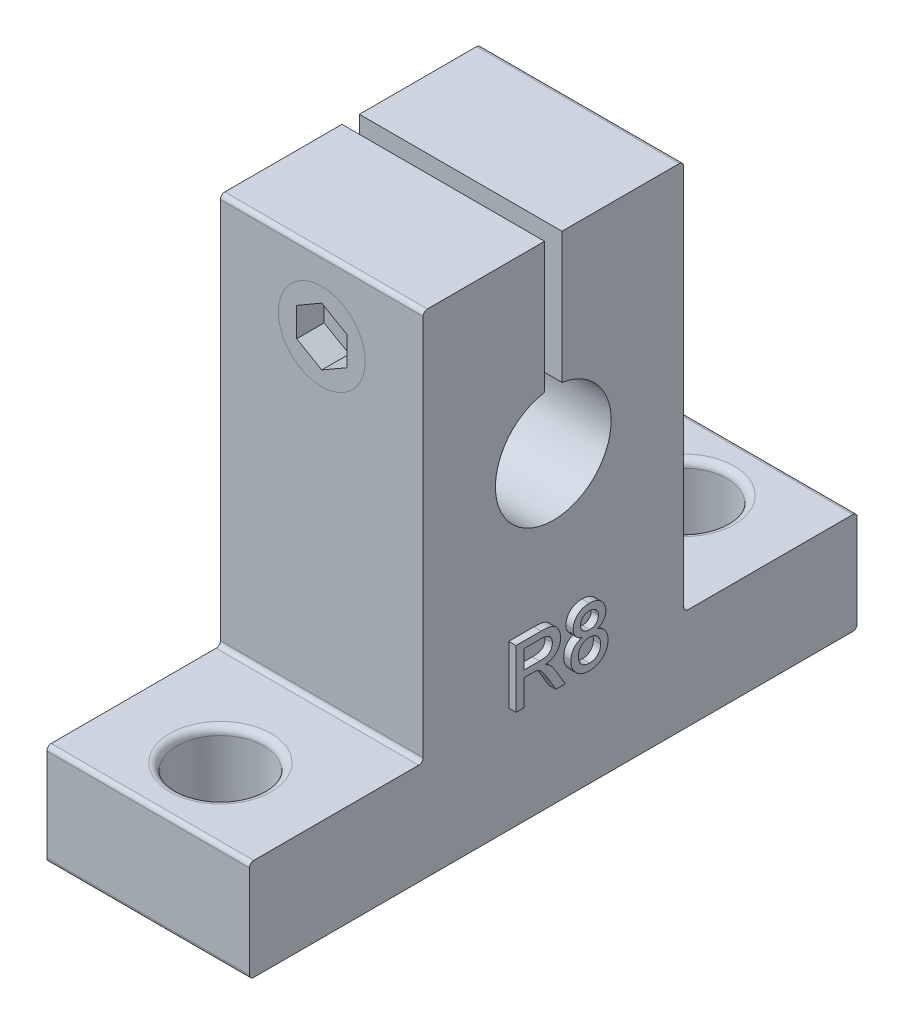
SolidWorks part; units mm, degrees
ref_plane "Спереди" through (0, 0, 0) normal (0, 0, 1) x (1, 0, 0)
ref_plane "Сверху" through (0, 0, 0) normal (0, 1, 0) x (1, 0, 0)
ref_plane "Справа" through (0, 0, 0) normal (1, 0, 0) x (0, 0, -1)
ref_plane "Плоскость1" through (0, 0, 0) normal (1, 0, 0) x (0, 0, -1)
sketch "Эскиз1" plane through (0, 0, 0) normal (1, 0, 0) x (0, 0, -1)
  line L0 (0.3, 7) -> (11.7, 7)
  line L1 (0.3, 0) -> (41.7, 0)
  line L2 (0, 0.3) -> (0, 6.7)
  line L4 (42, 0.3) -> (42, 6.7)
  line L5 (21, 0) -> (21, 7) construction
  line L6 (41.7, 7) -> (30.3, 7)
  line L7 (12, 7.3) -> (12, 33.7)
  line L8 (12.3, 34) -> (29.7, 34)
  line L9 (30, 33.7) -> (30, 7.3)
  line L10 (21, 34) -> (21, 21) construction
  circle A0 centre (21, 21) radius 4
  arc A1 (30.3, 7) -> (30, 7.3) centre (30.3, 7.3) cw
  arc A2 (11.7, 7) -> (12, 7.3) centre (11.7, 7.3) ccw
  arc A3 (41.7, 0) -> (42, 0.3) centre (41.7, 0.3) ccw
  arc A4 (42, 6.7) -> (41.7, 7) centre (41.7, 6.7) ccw
  arc A5 (30, 33.7) -> (29.7, 34) centre (29.7, 33.7) ccw
  arc A6 (12, 33.7) -> (12.3, 34) centre (12.3, 33.7) cw
  arc A7 (0, 0.3) -> (0.3, 0) centre (0.3, 0.3) ccw
  arc A8 (0, 6.7) -> (0.3, 7) centre (0.3, 6.7) cw
  point P16 (30, 7)
  point P19 (12, 7)
  point P22 (42, 0)
  point P25 (42, 7)
  point P30 (12, 34)
  point P33 (0, 0)
  point P36 (0, 7)
  dimension "D5" = 8
  dimension "D6" = 0.3
  dimension "D1" = 42
  dimension "D2" = 7
  dimension "D3" = 12
  dimension "D4" = 27
extrude "Бобышка-Вытянуть1" add sketch "Эскиз1" along normal blind 14
ref_plane "Плоскость2" through (14, 0, 0) normal (1, 0, 0) x (0, 0, -1)
sketch "Эскиз2" plane through (14, 0, 0) normal (1, 0, 0) x (0, 0, -1)
  line L0 (21, 21) -> (21, 34)
extrude "Вырез-Вытянуть-Тонкостенный1" cut sketch "Эскиз2" against normal blind 14 and the other way through all thin thin type mid plane wall 1.2
ref_plane "Плоскость3" through (0, 7, 0) normal (0, 1, 0) x (1, 0, 0)
sketch "Эскиз3" plane through (0, 7, 0) normal (0, 1, 0) x (1, 0, 0)
  line L0 (0, 0) -> (14, 0) construction
  line L1 (7, 40) -> (7, 34) construction
  line L2 (7, 0) -> (7, 2) construction
  line L3 (7, 2) -> (7, 8) construction
  line L4 (0, 0) -> (0, 42) construction
  line L5 (0, 42) -> (0, 21) construction
  line L6 (0, 21) -> (14, 21) construction
  line L7 (14, 17) -> (14, 25) construction
  line L8 (7, 42) -> (7, 40) construction
  line L9 (0, 42) -> (14, 42) construction
  circle A0 centre (7, 5) radius 3
  circle A2 centre (7, 37) radius 3
  dimension "D1" = 6
  dimension "D2" = 2
extrude "Вырез-Вытянуть1" cut sketch "Эскиз3" against normal blind 14
ref_plane "Плоскость4" through (0, 0, -12) normal (0, 0, 1) x (1, 0, 0)
sketch "Эскиз4" plane through (0, 0, -12) normal (0, 0, 1) x (1, 0, 0)
  line L0 (0, 34) -> (14, 34) construction
  line L1 (14, 34) -> (7, 34) construction
  line L2 (7, 34) -> (7, 31) construction
  line L3 (7, 31) -> (7, 27) construction
  circle A0 centre (7, 29) radius 2
  dimension "D1" = 3
  dimension "D2" = 4
extrude "Вырез-Вытянуть2" cut sketch "Эскиз4" against normal blind 24
ref_plane "Плоскость5" through (0, 0, -12) normal (0, 0, 1) x (1, 0, 0)
sketch "Эскиз5" plane through (0, 0, -12) normal (0, 0, 1) x (1, 0, 0)
  line L0 (7, 34) -> (7, 32) construction
  line L1 (14, 34) -> (0, 34) construction
  circle A0 centre (7, 29) radius 3
extrude "Вырез-Вытянуть3" cut sketch "Эскиз5" against normal blind 5
ref_plane "Плоскость6" through (0, 0, -14) normal (0, 0, 1) x (1, 0, 0)
sketch "Эскиз6" plane through (0, 0, -14) normal (0, 0, 1) x (1, 0, 0)
  circle A0 centre (7, 29) radius 2
  dimension "D1" = 4
extrude "Бобышка-Вытянуть2" add sketch "Эскиз6" along normal blind 0.1 and the other way blind 15 separate body
fillet "Скругление1" radius 0.5 1 edges at (9, 29, -30)
ref_plane "Плоскость7" through (0, 0, -17) normal (0, 0, 1) x (1, 0, 0)
sketch "Эскиз7" plane through (0, 0, -17) normal (0, 0, 1) x (1, 0, 0)
  line L1 (7, 27) -> (8.7321, 28)
  line L2 (8.7321, 28) -> (8.7321, 30)
  line L3 (8.7321, 30) -> (7, 31)
  line L4 (7, 31) -> (5.2679, 30)
  line L5 (5.2679, 30) -> (5.2679, 28)
  line L6 (5.2679, 28) -> (7, 27)
  circle A0 centre (7, 29) radius 3
  circle A1 centre (7, 29) radius 1.7321 construction
  dimension "D1" = 6
extrude "Бобышка-Вытянуть3" add sketch "Эскиз7" along normal blind 5 separate body
fillet "Скругление2" radius 0.5 1 edges at (7, 7, -2)
fillet "Скругление3" radius 0.5 1 edges at (7, 7, -40)
ref_plane "Плоскость8" through (14, 0, 0) normal (1, 0, 0) x (0, 0, -1)
sketch "Эскиз8" plane through (14, 0, 0) normal (1, 0, 0) x (0, 0, -1)
  line L0 (12, 7.3) -> (30, 7.3) construction
  text T0 "R8"
extrude "Бобышка-Вытянуть4" add sketch "Эскиз8" along normal blind 0.5
